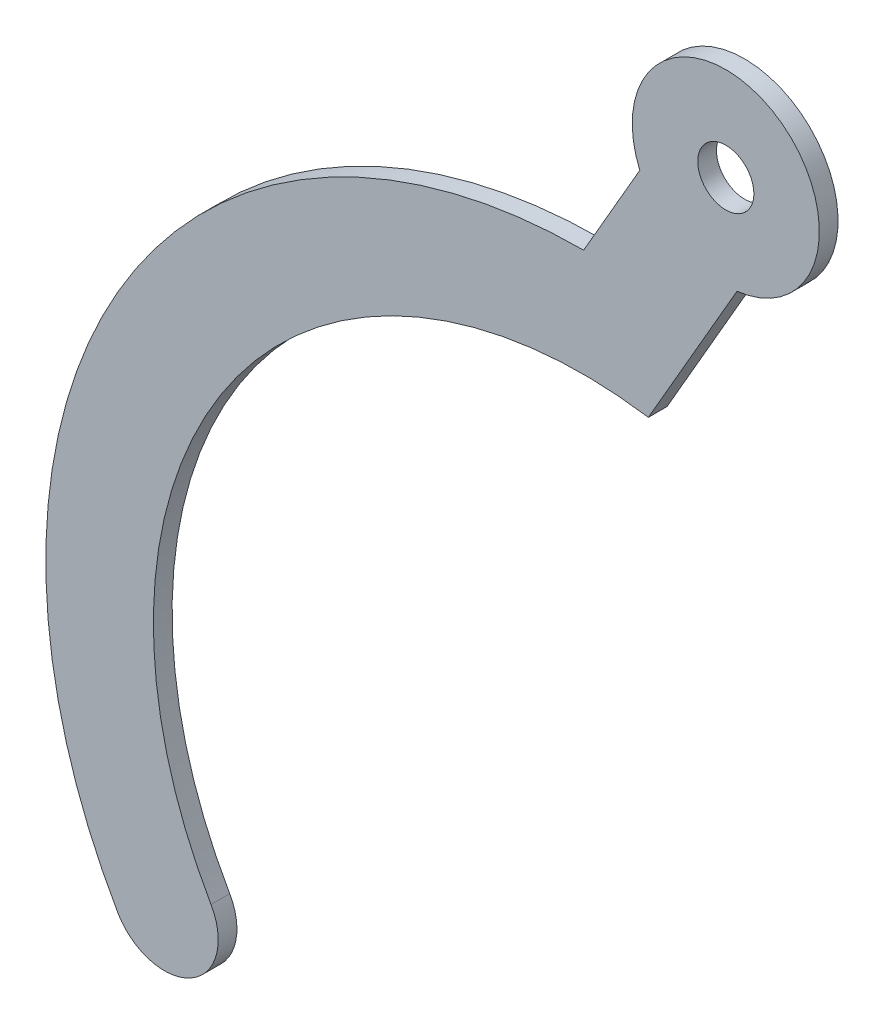
SolidWorks part; units mm, degrees
ref_plane "前视基准面" through (0, 0, 0) normal (0, 0, 1) x (1, 0, 0)
ref_plane "上视基准面" through (0, 0, 0) normal (0, 1, 0) x (1, 0, 0)
ref_plane "右视基准面" through (0, 0, 0) normal (1, 0, 0) x (0, 0, -1)
sketch "草图1" plane through (0, 0, 0) normal (0, 0, 1) x (1, 0, 0)
  line L7 (0, 57.5) -> (6, 67.8923)
  line L10 (16.3923, 61.8923) -> (6.9151, 45.4773)
  arc A0 (0, 57.5) -> (-49.7965, -28.75) centre (0, 0) ccw
  arc A2 (6.9151, 45.4773) -> (-39.8372, -23) centre (0, 0) ccw
  arc A3 (-49.7965, -28.75) -> (-39.8372, -23) centre (-44.8168, -25.875) ccw
  circle A4 centre (15.1962, 71.8205) radius 3
  arc A5 (16.3923, 61.8923) -> (6, 67.8923) centre (15.1962, 71.8205) ccw
extrude "凸台-拉伸1" add sketch "草图1" along normal blind 2
